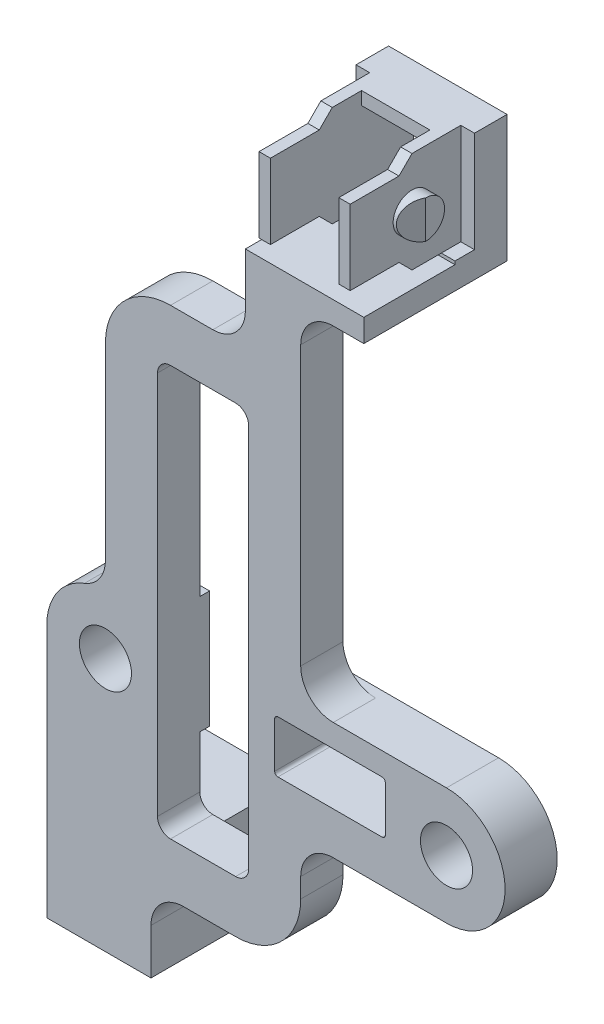
SolidWorks part; units mm, degrees
ref_plane "Front Plane" through (0, 0, 0) normal (0, 0, 1) x (1, 0, 0)
ref_plane "Top Plane" through (0, 0, 0) normal (0, 1, 0) x (1, 0, 0)
ref_plane "Right Plane" through (0, 0, 0) normal (1, 0, 0) x (0, 0, -1)
sketch "Sketch1" plane through (0, 0, 0) normal (0, 0, 1) x (1, 0, 0)
  line L0 (42.5, -2.5) -> (26.5, -2.5)
  line L1 (43, -2) -> (43, 5)
  line L2 (42.5, 5.5) -> (26.5, 5.5)
  line L3 (26, -2) -> (26, 5)
  line L5 (8, 42) -> (8, -17)
  line L10 (10, -19) -> (20, -19)
  line L16 (0, 13.0767) -> (0, 42)
  line L20 (-9, -39) -> (7, -39)
  line L30 (-9, 0) -> (-9, -39)
  line L31 (10, 44) -> (20, 44)
  line L32 (22, 42) -> (22, -17)
  line L36 (30, -17) -> (30, -14)
  line L37 (52.4, -9) -> (35, -9)
  line L38 (20, -27) -> (12, -27)
  line L39 (7, -32) -> (7, -39)
  line L51 (10, 52) -> (16.5, 52)
  line L55 (21.5, 81.25) -> (21.5, 57)
  line L61 (30, 56.75) -> (30, 14)
  line L62 (35, 9) -> (52.4, 9)
  line L66 (21.5, 81.25) -> (39.7, 81.25)
  line L67 (39.7, 81.25) -> (39.7, 61.75)
  line L68 (35.85, 79.25) -> (25.35, 79.25)
  line L69 (35.85, 79.25) -> (35.85, 67.75)
  line L70 (35.85, 67.75) -> (25.35, 67.75)
  line L71 (25.35, 79.25) -> (25.35, 67.75)
  line L72 (39.7, 61.75) -> (35, 61.75)
  circle A66 centre (0, 0) radius 4
  circle A67 centre (52.4, 0) radius 4
  arc A68 (43, 5) -> (42.5, 5.5) centre (42.5, 5) ccw
  arc A69 (42.5, -2.5) -> (43, -2) centre (42.5, -2) ccw
  arc A70 (26.5, -2.5) -> (26, -2) centre (26.5, -2) cw
  arc A71 (26.5, 5.5) -> (26, 5) centre (26.5, 5) ccw
  arc A73 (52.4, -9) -> (52.4, 9) centre (52.4, 0) ccw
  arc A75 (20, 44) -> (22, 42) centre (20, 42) cw
  arc A76 (8, 42) -> (10, 44) centre (10, 42) cw
  arc A77 (20, -19) -> (22, -17) centre (20, -17) ccw
  arc A78 (8, -17) -> (10, -19) centre (10, -17) ccw
  arc A79 (-3.2143, 8.4064) -> (-9, 0) centre (0, 0) ccw
  arc A80 (10, 52) -> (0, 42) centre (10, 42) ccw
  arc A82 (0, 13.0767) -> (-3.2143, 8.4064) centre (-5, 13.0767) cw
  arc A87 (20, -27) -> (30, -17) centre (20, -17) ccw
  arc A88 (30, -14) -> (35, -9) centre (35, -14) cw
  arc A89 (12, -27) -> (7, -32) centre (12, -32) ccw
  arc A91 (21.5, 57) -> (16.5, 52) centre (16.5, 57) cw
  arc A92 (30, 14) -> (35, 9) centre (35, 14) ccw
  arc A93 (35, 61.75) -> (30, 56.75) centre (35, 56.75) ccw
extrude "Boss-Extrude1" add sketch "Sketch1" along normal blind 22
sketch "Sketch3" plane through (0, 0, 0) normal (0, 0, -1) x (-1, 0, 0)
  line L2 (-21.5, 61.75) -> (-35, 61.75)
  line L5 (-12, -27) -> (-20, -27)
  line L8 (9, -23.75) -> (-7, -23.75)
  line L9 (-7, -32) -> (-7, -23.75)
  line L12 (-16.5, 52) -> (-10, 52)
  line L14 (-21.5, 57) -> (-21.5, 61.75)
  line L16 (-30, 56.75) -> (-30, 14)
  line L18 (-52.4, 9) -> (-35, 9)
  line L19 (-52.4, -9) -> (-35, -9)
  line L21 (-30, -14) -> (-30, -17)
  line L22 (0, 42) -> (0, 13.0767)
  line L24 (9, 0) -> (9, -23.75)
  arc A0 (-7, -32) -> (-12, -27) centre (-12, -32) ccw
  arc A1 (-30, -17) -> (-20, -27) centre (-20, -17) ccw
  arc A2 (-30, -14) -> (-35, -9) centre (-35, -14) ccw
  arc A3 (-52.4, 9) -> (-52.4, -9) centre (-52.4, 0) ccw
  arc A6 (0, 42) -> (-10, 52) centre (-10, 42) ccw
  arc A7 (-21.5, 57) -> (-16.5, 52) centre (-16.5, 57) ccw
  arc A9 (9, 0) -> (3.2143, 8.4064) centre (0, 0) ccw
  arc A10 (0, 13.0767) -> (3.2143, 8.4064) centre (5, 13.0767) ccw
  arc A11 (-35, 9) -> (-30, 14) centre (-35, 14) ccw
  arc A12 (-30, 56.75) -> (-35, 61.75) centre (-35, 56.75) ccw
  point P5 (0, 0)
extrude "Cut-Extrude1" cut sketch "Sketch3" against normal offset from surface (14 mm away) 8 up to face at (15, 12.5, 22)
sketch "Sketch4" plane through (39.7, 0, 0) normal (1, 0, 0) x (0, 0, -1)
  line L1 (-22, 81.25) -> (-5, 81.25)
  line L2 (-22, 81.25) -> (-22, 65.75)
  line L3 (-22, 65.75) -> (-5, 65.75)
  line L4 (-5, 81.25) -> (-5, 65.75)
  circle A0 centre (-12.5, 73.5) radius 2.9
sketch "Sketch5" plane through (21.5, 0, 0) normal (-1, 0, 0) x (0, 0, 1)
  line L3 (5, 81.25) -> (5, 65.75)
  line L4 (22, 65.75) -> (5, 65.75)
  line L5 (22, 81.25) -> (22, 65.75)
  line L6 (22, 81.25) -> (5, 81.25)
  circle A1 centre (12.5, 73.5) radius 2.9
extrude "Cut-Extrude2" cut sketch "Sketch5" against normal blind 2.1
extrude "Cut-Extrude3" cut sketch "Sketch4" against normal blind 2.1
sketch "Sketch6" plane through (21.5, 0, 0) normal (-1, 0, 0) x (0, 0, 1)
  line L1 (22, 81.25) -> (5, 81.25) construction
  line L3 (5, 65.75) -> (22, 65.75) construction
  line L7 (12.5, 81.25) -> (14.5, 79.25)
  line L8 (14.5, 79.25) -> (22, 79.25)
  line L9 (22, 65.75) -> (22, 81.25) construction
  line L10 (12.5, 65.75) -> (14.5, 67.75)
  line L11 (14.5, 67.75) -> (22, 67.75)
  line L12 (12.5, 81.25) -> (22, 81.25)
  line L13 (22, 81.25) -> (22, 79.25)
  line L14 (12.5, 65.75) -> (22, 65.75)
  line L15 (22, 65.75) -> (22, 67.75)
extrude "Cut-Extrude4" cut sketch "Sketch6" against normal up to surface (18.2 mm away)
sketch "Sketch7" plane through (0, 0, 22) normal (0, 0, 1) x (1, 0, 0)
  line L0 (25.35, 81.25) -> (35.85, 81.25)
  line L5 (21.5, 65.75) -> (21.5, 65.25)
  line L7 (21.5, 65.25) -> (39.7, 65.25)
  line L9 (39.7, 65.25) -> (39.7, 65.75)
  line L10 (25.35, 81.25) -> (25.35, 65.75)
  line L12 (25.35, 65.75) -> (21.5, 65.75)
  line L13 (35.85, 81.25) -> (35.85, 65.75)
  line L15 (35.85, 65.75) -> (39.7, 65.75)
extrude "Cut-Extrude5" cut sketch "Sketch7" against normal offset from surface (14 mm away) 3 up to face at (22.55, 73.5, 5)
sketch "Sketch8" plane through (0, 81.25, 0) normal (0, 1, 0) x (1, 0, 0)
  line L0 (21.5, -12.5) -> (23.1, -15.4)
  line L1 (21.5, -15.4) -> (23.6, -15.4) construction
  line L2 (21.5, -9.6) -> (21.5, -15.4) construction
  line L4 (37.6, -15.4) -> (39.7, -15.4) construction
  line L8 (21.5, -15.4) -> (23.1, -15.4)
  line L10 (39.7, -15.4) -> (39.7, -9.6) construction
  line L12 (39.7, -15.4) -> (38.1, -15.4)
  line L13 (21.5, -12.5) -> (21.5, -15.4)
  line L14 (39.7, -12.5) -> (39.7, -15.4)
  line L15 (39.7, -12.5) -> (38.1, -15.4)
extrude "Cut-Extrude6" cut sketch "Sketch8" against normal up to surface (15.5 mm away) up to face at (22.55, 65.75, 6.5)
sketch "Sketch10" plane through (0, 0, 14) normal (0, 0, -1) x (-1, 0, 0)
  line L0 (-35, 9) -> (2.1051, 9)
  line L1 (-30, 56.75) -> (-30, 14)
  line L2 (0, 42) -> (0, 13.0767)
  line L3 (-35, 61.75) -> (-21.5, 61.75)
  line L4 (-21.5, 61.75) -> (-21.5, 57)
  line L5 (-35, -9) -> (0, -9)
  line L6 (-16.5, 52) -> (-10, 52)
  line L7 (-20, -27) -> (-12, -27)
  line L9 (-7, -32) -> (-7, -23.75)
  line L10 (-7, -23.75) -> (9, -23.75)
  line L11 (9, -23.75) -> (9, 0)
  line L12 (-30, -14) -> (-30, -17)
  arc A0 (0, 13.0767) -> (3.2143, 8.4064) centre (5, 13.0767) ccw construction
  arc A1 (0, 13.0767) -> (2.1051, 9) centre (5, 13.0767) ccw
  arc A2 (-35, 9) -> (-30, 14) centre (-35, 14) ccw
  arc A3 (0, 42) -> (-10, 52) centre (-10, 42) ccw
  arc A4 (-30, 56.75) -> (-35, 61.75) centre (-35, 56.75) ccw
  arc A5 (-21.5, 57) -> (-16.5, 52) centre (-16.5, 57) ccw
  arc A6 (0, -9) -> (9, 0) centre (0, 0) ccw
  arc A7 (-30, -17) -> (-20, -27) centre (-20, -17) ccw
  arc A8 (-7, -32) -> (-12, -27) centre (-12, -32) ccw
  arc A9 (-30, -14) -> (-35, -9) centre (-35, -14) ccw
extrude "Cut-Extrude8" cut sketch "Sketch10" against normal blind 1.5
sketch "Sketch11" plane through (-9, 0, 0) normal (-1, 0, 0) x (0, 0, 1)
  line L0 (2.1, -31.25) -> (0, -31.25)
  line L1 (2.1, -25.5) -> (16.1, -25.5)
  line L2 (2.1, -25.5) -> (2.1, -37)
  line L3 (2.1, -37) -> (16.1, -37)
  line L4 (16.1, -25.5) -> (16.1, -37)
  line L5 (16.1, -31.25) -> (18.2, -31.25)
  line L8 (11, -37) -> (11, -39)
